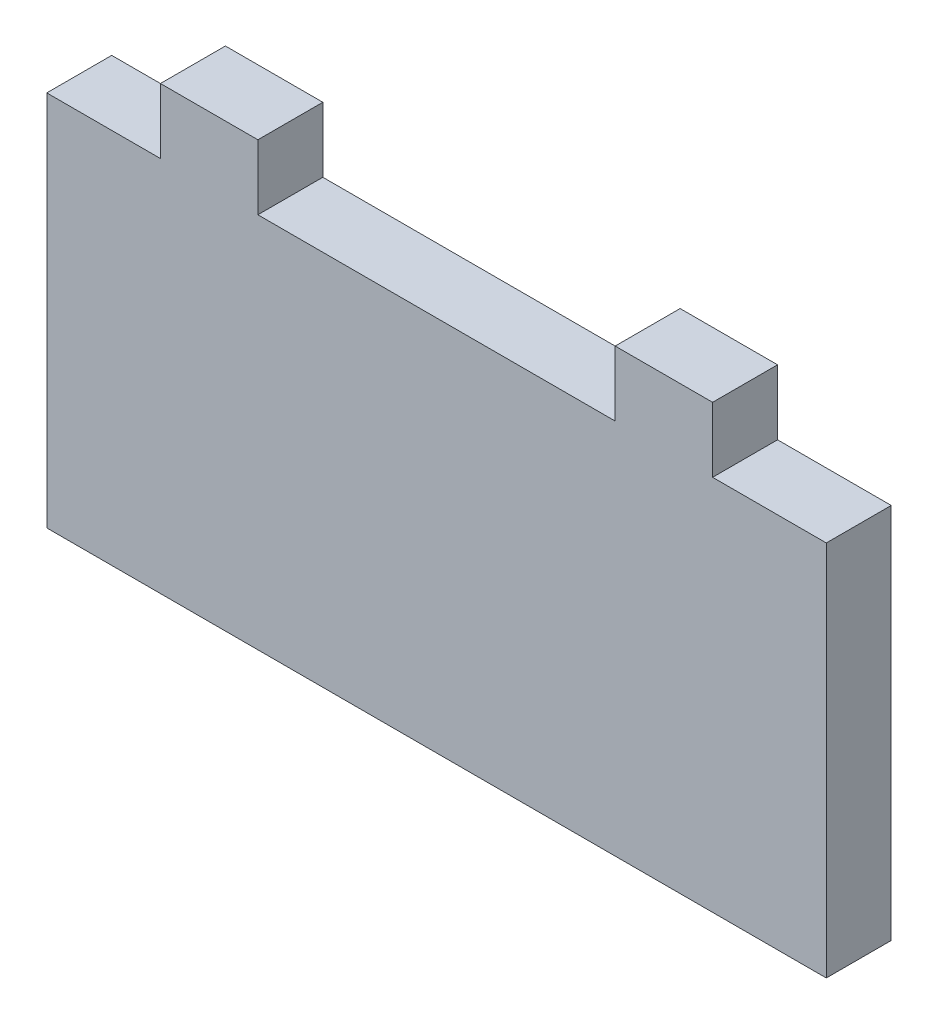
SolidWorks part; units mm, degrees
material "Acrylic (Medium-high impact)"
ref_plane "Front Plane" through (0, 0, 0) normal (0, 0, 1) x (1, 0, 0)
ref_plane "Top Plane" through (0, 0, 0) normal (0, 1, 0) x (1, 0, 0)
ref_plane "Right Plane" through (0, 0, 0) normal (1, 0, 0) x (0, 0, -1)
sketch "Sketch1" plane through (0, 0, 0) normal (0, 0, 1) x (1, 0, 0)
  line L0 (-53.975, 215.9) -> (-53.975, 228.6) construction
  line L1 (-76.2, 215.9) -> (-53.975, 215.9)
  line L2 (-76.2, 215.9) -> (-76.2, 142.24)
  line L3 (-76.2, 142.24) -> (76.2, 142.24)
  line L4 (76.2, 215.9) -> (76.2, 142.24)
  line L5 (-34.925, 228.6) -> (-53.975, 228.6) construction
  line L6 (-34.925, 215.9) -> (-34.925, 228.6) construction
  line L7 (34.925, 215.9) -> (34.925, 228.6) construction
  line L8 (53.975, 228.6) -> (34.925, 228.6) construction
  line L9 (53.975, 215.9) -> (53.975, 228.6) construction
  line L10 (-53.975, 215.9) -> (-53.975, 228.6)
  line L11 (-34.925, 228.6) -> (-53.975, 228.6)
  line L12 (-34.925, 215.9) -> (-34.925, 228.6)
  line L13 (34.925, 215.9) -> (34.925, 228.6)
  line L14 (53.975, 228.6) -> (34.925, 228.6)
  line L15 (53.975, 215.9) -> (53.975, 228.6)
  line L16 (-34.925, 215.9) -> (34.925, 215.9)
  line L17 (53.975, 215.9) -> (76.2, 215.9)
extrude "Extrude1" add sketch "Sketch1" against normal blind 12.7
sketch "Sketch2" plane through (0, 0, 0) normal (0, 0, 1) x (1, 0, 0)
  line L0 (-76.2, 142.24) -> (76.2, 142.24) construction
  line L1 (-25.4, 182.88) -> (25.4, 182.88)
  line L2 (-25.4, 182.88) -> (-25.4, 142.24)
  line L3 (-25.4, 142.24) -> (25.4, 142.24)
  line L4 (25.4, 182.88) -> (25.4, 142.24)
  point P6 (0, 182.88)
  dimension "D1" = 50.8
  dimension "D2" = 40.64
extrude "Cut-Extrude1" [suppressed] cut sketch "Sketch2" against normal through all
fillet "Fillet1" [suppressed] radius 6.4262
